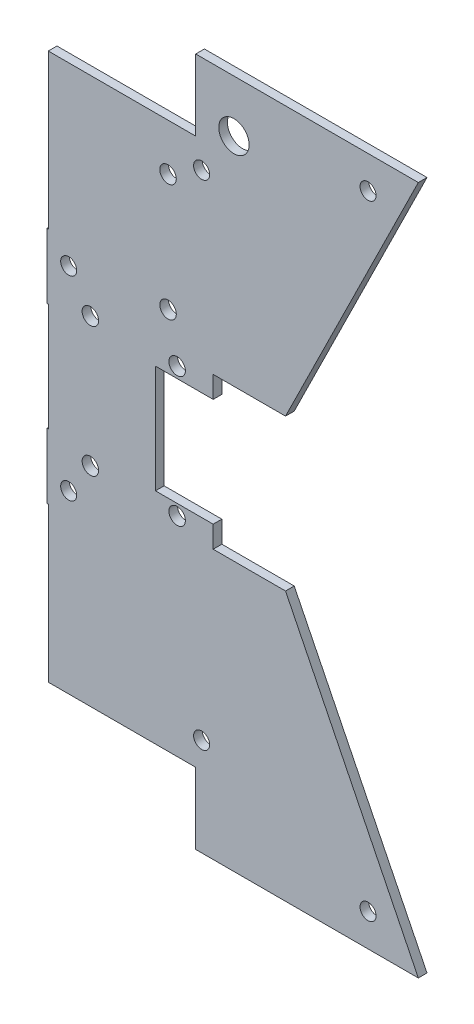
SolidWorks part; units mm, degrees
material "Thornel Mat VMA"
ref_plane "Front Plane" through (0, 0, 0) normal (0, 0, 1) x (1, 0, 0)
ref_plane "Top Plane" through (0, 0, 0) normal (0, 1, 0) x (1, 0, 0)
ref_plane "Right Plane" through (0, 0, 0) normal (1, 0, 0) x (0, 0, -1)
sketch "Sketch1" plane through (0, 0, 0) normal (0, 0, 1) x (1, 0, 0)
  line L0 (-2.9301, -104.5098) -> (-3.3149, -104.5098)
  line L1 (-3.3149, -72.8868) -> (-2.9301, -72.8868)
  line L78 (45.3299, -66.5368) -> (45.3299, -72.8868)
  line L79 (45.3299, -104.5098) -> (45.3299, -110.8598)
  line L80 (66.5174, -66.5368) -> (105.3971, 12.1397)
  line L81 (105.3971, 12.1397) -> (38.7094, 12.1397)
  line L88 (38.7094, 12.1397) -> (38.7094, -8.6883)
  line L89 (-2.9301, -8.6883) -> (38.7094, -8.6883)
  line L90 (-3.3149, -53.8368) -> (-2.9301, -53.8368)
  line L91 (-2.9301, -53.8368) -> (-2.9301, -8.6883)
  line L92 (-3.3149, -66.5368) -> (-3.3149, -53.8368)
  line L93 (-3.3149, -72.8868) -> (-3.3149, -66.5368)
  line L94 (-2.9301, -104.5098) -> (-2.9301, -72.8868)
  line L95 (-3.3149, -110.8598) -> (-3.3149, -104.5098)
  line L96 (66.5174, -110.8598) -> (105.3971, -189.5363)
  line L97 (105.3971, -189.5363) -> (38.7094, -189.5363)
  line L98 (38.7094, -189.5363) -> (38.7094, -168.7083)
  line L99 (-2.9301, -168.7083) -> (38.7094, -168.7083)
  line L106 (-3.3149, -110.8598) -> (-3.3149, -123.5598)
  line L107 (-3.3149, -123.5598) -> (-2.9301, -123.5598)
  line L108 (66.5174, -110.8598) -> (45.3299, -110.8598)
  line L109 (45.3299, -66.5368) -> (66.5174, -66.5368)
  line L110 (45.3299, -104.5098) -> (45.3299, -72.8868)
  line L111 (-2.9301, -123.5598) -> (-2.9301, -168.7083)
  circle A0 centre (90.6739, 2.6147) radius 2.3495
  circle A1 centre (41.9566, -16.4353) radius 2.3495
  circle A2 centre (3.0351, -60.1868) radius 2.3495
  circle A3 centre (3.0351, -117.2098) radius 2.3495
  circle A4 centre (41.9566, -160.9613) radius 2.3495
  circle A5 centre (90.6739, -180.0113) radius 2.3495
  circle A6 centre (51.4094, -3.1003) radius 4.445
  point P2 (90.6739, 2.6147)
  point P4 (41.9566, -16.4353)
  point P6 (3.0351, -60.1868)
  point P8 (3.0351, -117.2098)
  point P10 (41.9566, -160.9613)
  point P11 (90.6739, -180.0113)
  dimension "D2" = 4.699
  dimension "D5" = 8.89
  dimension "D1" = 66.6876
  dimension "D3" = 12.7
  dimension "D4" = 15.24
  dimension "D6" = 48.26
extrude "Boss-Extrude1" add sketch "Sketch1" along normal blind 2.54
sketch "Sketch2" plane through (0, 0, 2.54) normal (0, 0, 1) x (1, 0, 0)
  line L0 (-3.3149, -53.8368) -> (-3.3149, -72.8868) construction
  line L1 (45.3299, -66.5368) -> (66.5174, -66.5368) construction
  line L2 (45.3299, -88.6983) -> (-2.9301, -88.6983) construction
  line L3 (45.3299, -110.8598) -> (45.3299, -66.5368) construction
  line L4 (-2.9301, -72.8868) -> (-2.9301, -104.5098) construction
  circle A0 centre (9.3851, -69.7118) radius 2.413
  circle A2 centre (34.7851, -69.7118) radius 2.413
  circle A4 centre (34.7851, -107.6848) radius 2.413
  circle A6 centre (9.3851, -107.6848) radius 2.413
  dimension "D1" = 4.826
  dimension "D2" = 25.4
  dimension "D3" = 4.826
  dimension "D5" = 12.7
  dimension "D7" = 3.175
extrude "Cut-Extrude1" cut sketch "Sketch2" against normal through all
sketch "Sketch3" plane through (0, 0, 2.54) normal (0, 0, 1) x (1, 0, 0)
  line L0 (45.3299, -110.8598) -> (45.3299, -66.5368) construction
  line L1 (45.3299, -72.8868) -> (28.4351, -72.8868)
  line L2 (45.3299, -72.8868) -> (45.3299, -104.5098)
  line L3 (45.3299, -104.5098) -> (28.4351, -104.5098)
  line L4 (28.4351, -72.8868) -> (28.4351, -104.5098)
  line L5 (45.3299, -66.5368) -> (66.5174, -66.5368) construction
  line L6 (66.5174, -110.8598) -> (45.3299, -110.8598) construction
  circle A1 centre (9.3851, -69.7118) radius 2.413 construction
  dimension "D3" = 19.05
  dimension "D1" = 6.35
  dimension "D2" = 6.35
extrude "Cut-Extrude2" cut sketch "Sketch3" against normal through all
sketch "Sketch4" plane through (0, 0, 2.54) normal (0, 0, 1) x (1, 0, 0)
  line L0 (-2.9301, -168.7083) -> (38.7094, -168.7083) construction
  line L1 (27.4577, 15.7469) -> (40.2334, 15.7469)
  line L2 (27.4577, 15.7469) -> (27.4577, -8.6883)
  line L3 (27.4577, -8.6883) -> (40.2334, -8.6883)
  line L4 (40.2334, 15.7469) -> (40.2334, -8.6883)
  line L5 (0, -197.042) -> (40.2334, -197.042)
  line L6 (0, -197.042) -> (0, -168.7083)
  line L7 (0, -168.7083) -> (40.2334, -168.7083)
  line L8 (40.2334, -197.042) -> (40.2334, -168.7083)
  line L9 (38.7094, -168.7083) -> (38.7094, -189.5363) construction
  line L10 (38.7094, -8.6883) -> (-2.9301, -8.6883) construction
  dimension "D1" = 1.524
extrude "Cut-Extrude3" cut sketch "Sketch4" against normal through all
sketch "Sketch5" plane through (0, 0, 0) normal (0, 0, -1) x (-1, 0, 0)
  line L0 (2.9301, -8.6883) -> (2.9301, -53.8368) construction
  line L1 (-40.2334, -8.6883) -> (2.9301, -8.6883) construction
  circle A0 centre (-32.1219, -22.4043) radius 2.413
  circle A1 centre (-32.1219, -56.6943) radius 2.413
  dimension "D4" = 4.826
  dimension "D1" = 35.052
  dimension "D2" = 13.716
  dimension "D3" = 34.29
extrude "Cut-Extrude4" cut sketch "Sketch5" against normal through all
